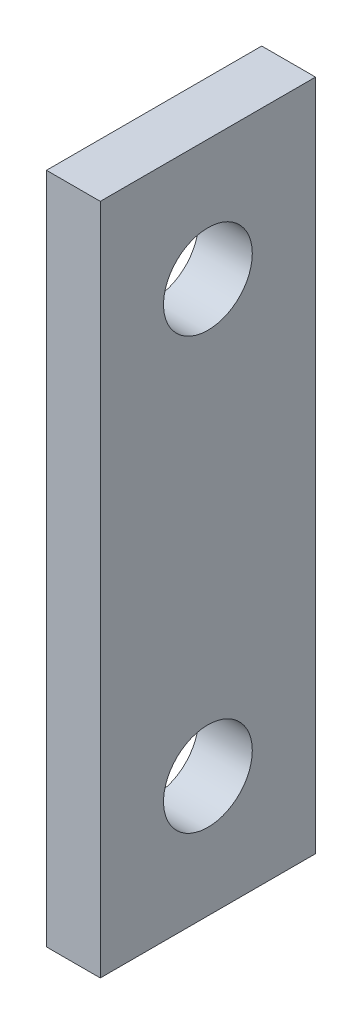
SolidWorks part; units mm, degrees
ref_plane "Front Plane" through (0, 0, 0) normal (1, 0, 0) x (0, 1, 0)
ref_plane "Top Plane" through (0, 0, 0) normal (0, 0, 1) x (0, 1, 0)
ref_plane "Right Plane" through (0, 0, 0) normal (0, 1, 0) x (-1, 0, 0)
sketch "Sketch1" plane through (0, 0, 0) normal (1, 0, 0) x (0, 1, 0)
  line L0 (0, 0) -> (53651.801, 0) construction
  line L1 (-62.5, 20) -> (62.5, 20)
  line L2 (-62.5, 20) -> (-62.5, -20)
  line L3 (-62.5, -20) -> (62.5, -20)
  line L4 (62.5, 20) -> (62.5, -20)
  line L7 (0, 0) -> (0, 53651.801) construction
  circle A0 centre (-40, 0) radius 8.25
  circle A1 centre (40, 0) radius 8.25
  point P0 (0, 0)
  dimension "D3" = 16.5
  dimension "D4" = 80
  dimension "D1" = 40
  dimension "D2" = 125
  dimension "D5" = 80
extrude "Boss-Extrude1" add sketch "Sketch1" along normal mid plane 10
